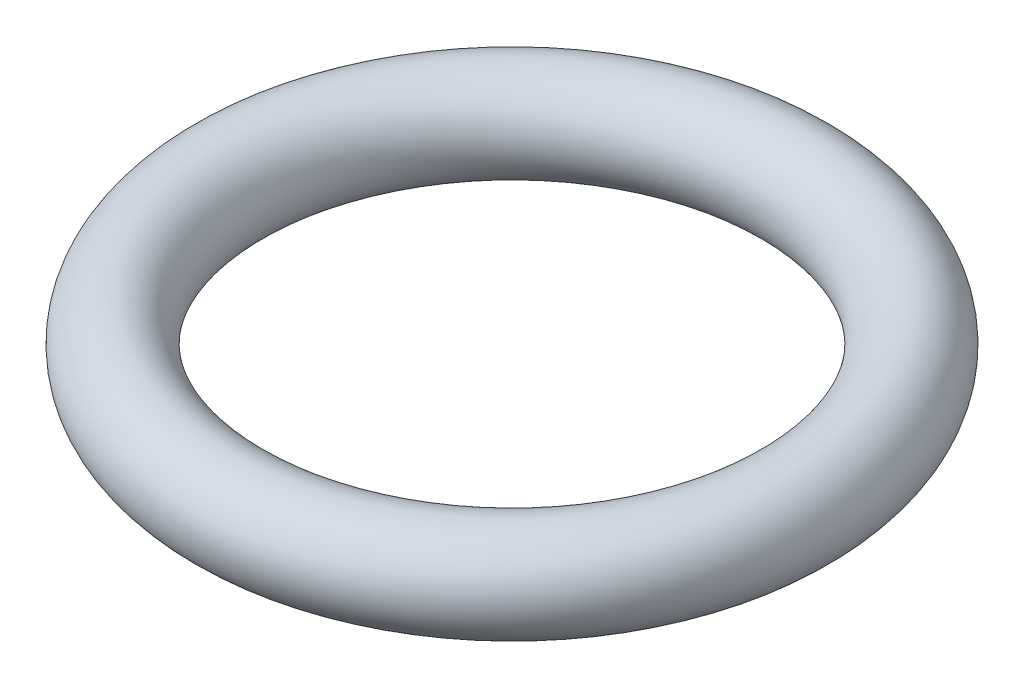
SolidWorks part; units mm, degrees
ref_plane "Front Plane" through (0, 0, 0) normal (0, 0, 1) x (1, 0, 0)
ref_plane "Top Plane" through (0, 0, 0) normal (0, 1, 0) x (1, 0, 0)
ref_plane "Right Plane" through (0, 0, 0) normal (1, 0, 0) x (0, 0, -1)
sketch "Sketch1" plane through (0, 0, 0) normal (0, 0, 1) x (1, 0, 0)
  line L0 (0, 0) -> (0, 1.5916) construction
  circle A0 centre (3, 0) radius 0.5
  dimension "D1" = 1
  dimension "D2" = 3
revolve "Revolve1" add sketch "Sketch1" angle 360 about L0
